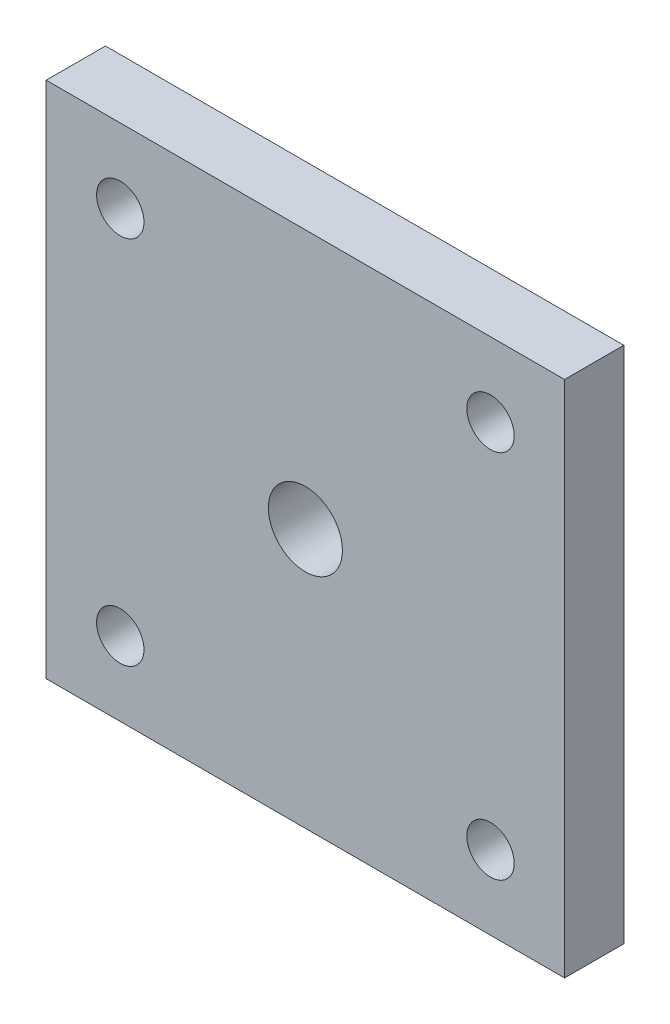
SolidWorks part; units mm, degrees
ref_plane "Front Plane" through (0, 0, 0) normal (0, 0, 1) x (1, 0, 0)
ref_plane "Top Plane" through (0, 0, 0) normal (0, 1, 0) x (1, 0, 0)
ref_plane "Right Plane" through (0, 0, 0) normal (1, 0, 0) x (0, 0, -1)
sketch "Sketch1" plane through (0, 0, 0) normal (0, 0, 1) x (1, 0, 0)
  line L1 (17.5, 17.5) -> (-17.5, 17.5)
  line L2 (17.5, 17.5) -> (17.5, -17.5)
  line L3 (17.5, -17.5) -> (-17.5, -17.5)
  line L4 (-17.5, 17.5) -> (-17.5, -17.5)
  line L5 (17.5, 17.5) -> (-17.5, -17.5) construction
  line L6 (17.5, -17.5) -> (-17.5, 17.5) construction
  point P0 (0, 0)
  dimension "D1" = 35
  dimension "D2" = 35
extrude "Boss-Extrude1" add sketch "Sketch1" along normal blind 4
sketch "Sketch2" plane through (0, 0, 4) normal (0, 0, 1) x (1, 0, 0)
  circle A0 centre (0, 0) radius 2.5
  dimension "D1" = 5
sketch "Sketch3" plane through (0, 0, 4) normal (0, 0, 1) x (1, 0, 0)
  line L1 (12.5, 12.5) -> (-12.5, 12.5) construction
  line L2 (12.5, 12.5) -> (12.5, -12.5) construction
  line L3 (12.5, -12.5) -> (-12.5, -12.5) construction
  line L4 (-12.5, 12.5) -> (-12.5, -12.5) construction
  line L5 (12.5, 12.5) -> (-12.5, -12.5) construction
  line L6 (12.5, -12.5) -> (-12.5, 12.5) construction
  circle A0 centre (-12.5, 12.5) radius 1.6
  circle A1 centre (12.5, 12.5) radius 1.6
  circle A2 centre (12.5, -12.5) radius 1.6
  circle A3 centre (-12.5, -12.5) radius 1.6
  point P0 (0, 0)
  dimension "D3" = 3.2
  dimension "D1" = 25
extrude "Dowel cut" cut sketch "Sketch3" against normal through all
extrude "Screw cut" cut sketch "Sketch2" against normal through all
